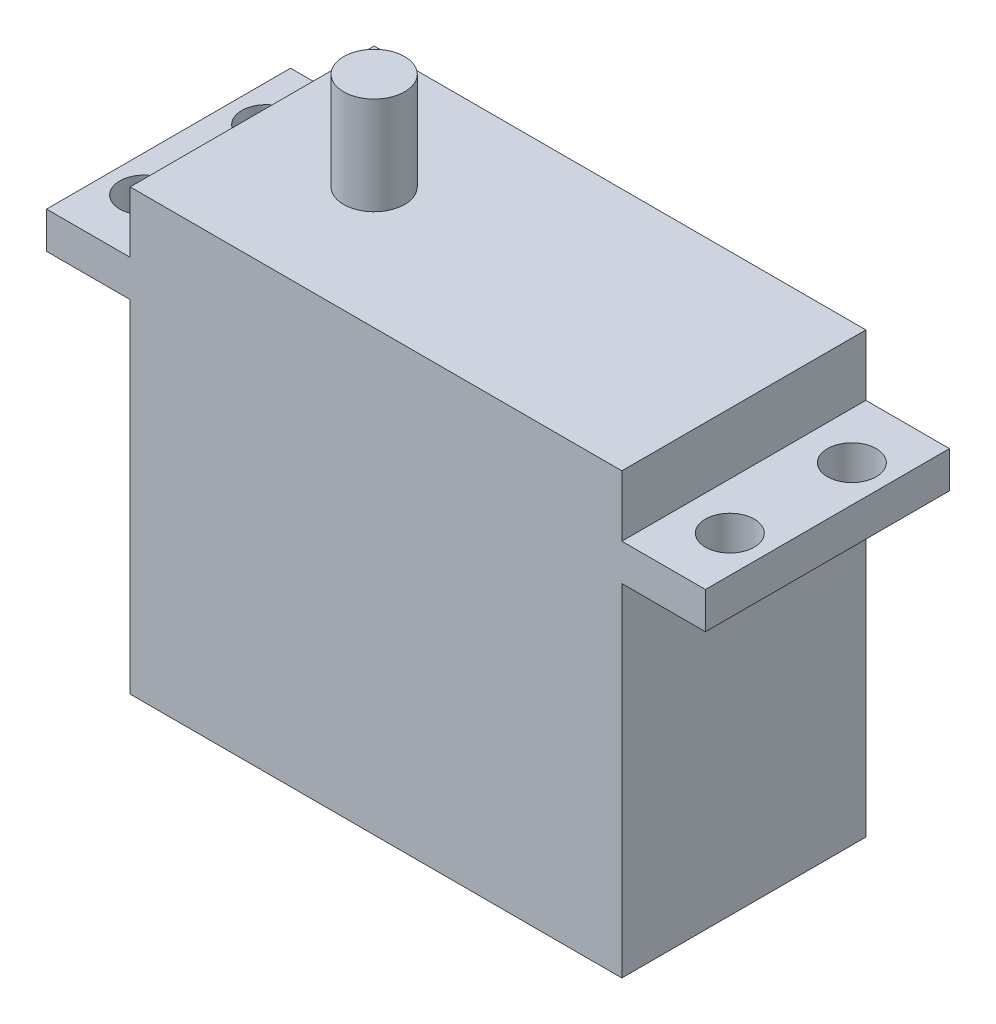
SolidWorks part; units mm, degrees
ref_plane "Front Plane" through (0, 0, 0) normal (0, 0, 1) x (1, 0, 0)
ref_plane "Top Plane" through (0, 0, 0) normal (0, 1, 0) x (1, 0, 0)
ref_plane "Right Plane" through (0, 0, 0) normal (1, 0, 0) x (0, 0, -1)
sketch "Sketch1" plane through (0, 0, 0) normal (0, 1, 0) x (1, 0, 0)
  line L0 (0, 0) -> (0, -20)
  line L1 (0, -20) -> (40.3, -20)
  line L2 (40.3, -20) -> (40.3, 0)
  line L3 (40.3, 0) -> (0, 0)
  dimension "D1" = 40.3
  dimension "D2" = 20
extrude "Boss-Extrude1" add sketch "Sketch1" along normal blind 28
ref_plane "SERVO_ATTACHMENT_PLANE" through (0, 28, 0) normal (0, 1, 0) x (1, 0, 0)
sketch "Sketch2" plane through (0, 28, 0) normal (0, 1, 0) x (1, 0, 0)
  line L0 (20.15, 0) -> (-3.85, 0) construction
  line L1 (40.3, 0) -> (0, 0) construction
  line L2 (-3.85, 0) -> (-3.85, -5) construction
  line L3 (-3.85, -5) -> (-3.85, -15) construction
  line L4 (20.15, 0) -> (-6.85, 0) construction
  line L5 (20.15, 0) -> (-6.85, 0)
  line L6 (20.15, -20) -> (-6.85, -20)
  line L7 (0, -20) -> (40.3, -20) construction
  line L8 (-6.85, -20) -> (-6.85, 0)
  line L9 (44.15, 0) -> (44.15, -5) construction
  line L10 (20.15, 0) -> (44.15, 0) construction
  line L11 (20.15, 0) -> (47.15, 0) construction
  line L12 (44.15, -5) -> (44.15, -15) construction
  line L13 (20.15, 0) -> (47.15, 0)
  line L14 (47.15, 0) -> (47.15, -20)
  line L15 (47.15, -20) -> (20.15, -20)
  circle A0 centre (-3.85, -5) radius 2
  circle A1 centre (-3.85, -15) radius 2
  circle A2 centre (44.15, -5) radius 2
  circle A3 centre (44.15, -15) radius 2
  dimension "D4" = 4
  dimension "D5" = 4
  dimension "D11" = 4
  dimension "D12" = 4
  dimension "D1" = 24
  dimension "D2" = 5
  dimension "D3" = 10
  dimension "D6" = 27
  dimension "D7" = 24
  dimension "D8" = 27
  dimension "D9" = 10
  dimension "D10" = 5
extrude "Boss-Extrude2" add sketch "Sketch2" along normal blind 3
sketch "Sketch3" plane through (0, 28, 0) normal (0, 1, 0) x (1, 0, 0)
  line L0 (0, 0) -> (0, -20)
  line L1 (0, -20) -> (40.3, -20)
  line L2 (40.3, -20) -> (40.3, 0)
  line L3 (40.3, 0) -> (0, 0)
  dimension "D1" = 40.3
  dimension "D2" = 20
extrude "Boss-Extrude3" add sketch "Sketch3" along normal blind 8
ref_plane "SERVO_TOP_PLANE" through (0, 36, 0) normal (0, 1, 0) x (1, 0, 0)
sketch "Sketch4" plane through (0, 36, 0) normal (0, 1, 0) x (1, 0, 0)
  line L0 (0, -10) -> (10, -10) construction
  line L1 (0, 0) -> (0, -20) construction
  circle A0 centre (10, -10) radius 2.5
  dimension "D2" = 5
  dimension "D1" = 10
extrude "Boss-Extrude4" add sketch "Sketch4" along normal blind 8
